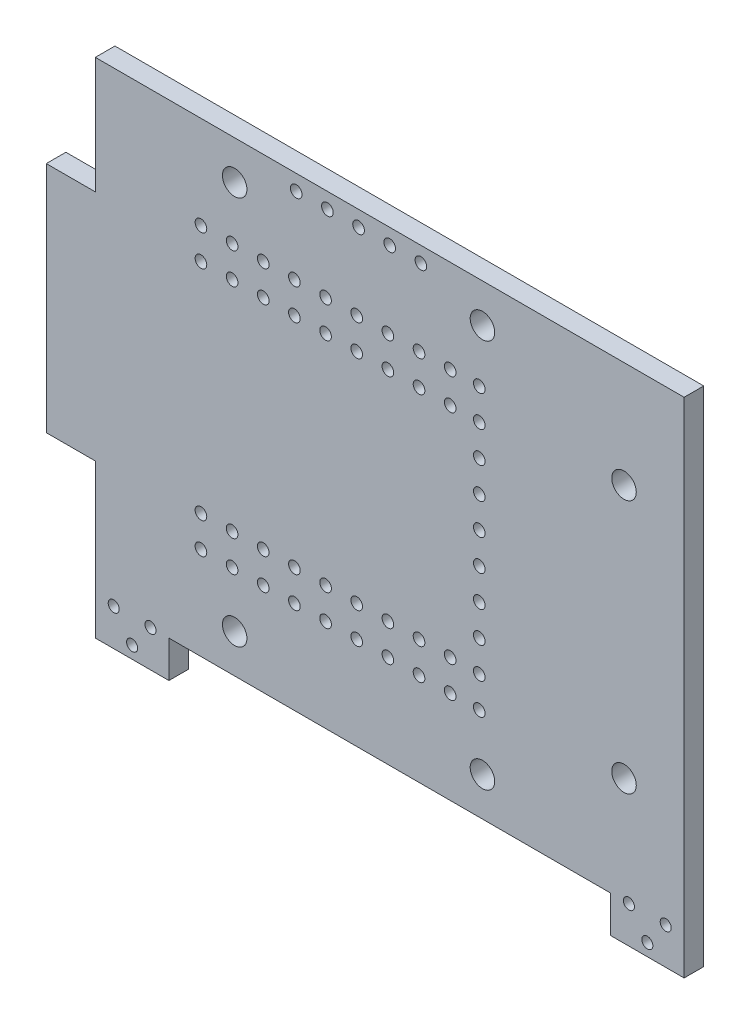
SolidWorks part; units mm, degrees
ref_plane "Front" through (0, 0, 0) normal (0, 0, 1) x (1, 0, 0)
ref_plane "Top" through (0, 0, 0) normal (0, 1, 0) x (1, 0, 0)
ref_plane "Right" through (0, 0, 0) normal (1, 0, 0) x (0, 0, -1)
sketch "草图1" plane through (0, 0, 0) normal (0, 0, 1) x (1, 0, 0)
  line L0 (0, 19.1903) -> (0, -26.9933) construction
  line L1 (-20.5, 19) -> (27.5, 19)
  line L2 (-20.5, 19) -> (-20.5, -19)
  line L3 (-20.5, -19) -> (27.5, -19)
  line L4 (27.5, 19) -> (27.5, -19)
  line L5 (-28.5476, 0) -> (37.8731, 0) construction
  dimension "D1" = 38
  dimension "D2" = 27.5
  dimension "D3" = 20.5
extrude "凸台-拉伸1" add sketch "草图1" against normal blind 1.6
ref_plane "基准面1" through (3.5, 0, 0) normal (1, 0, 0) x (0, 0, -1)
ref_plane "基准面2" through (0, 0, 0) normal (0, -1, 0) x (-1, 0, 0)
sketch "草图5" plane through (0, 0, 0) normal (0, 0, 1) x (1, 0, 0)
  circle A0 centre (-9.14, 15.85) radius 1
  circle A1 centre (11.06, 15.85) radius 1
  circle A2 centre (22.6, 10.35) radius 1
  circle A3 centre (22.6, -10.35) radius 1
  circle A4 centre (-11.89, 8.89) radius 0.475 construction
  circle A5 centre (-9.35, 8.89) radius 0.475 construction
  circle A6 centre (-6.81, 8.89) radius 0.475 construction
  circle A7 centre (-4.27, 8.89) radius 0.475 construction
  circle A8 centre (-11.89, 11.43) radius 0.475 construction
  circle A9 centre (-9.35, 11.43) radius 0.475 construction
  circle A10 centre (-6.81, 11.43) radius 0.475 construction
  circle A11 centre (-4.27, 11.43) radius 0.475 construction
  circle A12 centre (-1.73, 11.43) radius 0.475 construction
  circle A13 centre (0.81, 11.43) radius 0.475 construction
  circle A14 centre (3.35, 11.43) radius 0.475 construction
  circle A15 centre (-1.73, 8.89) radius 0.475 construction
  circle A16 centre (0.81, 8.89) radius 0.475 construction
  circle A17 centre (3.35, 8.89) radius 0.475 construction
  circle A18 centre (5.89, 8.89) radius 0.475 construction
  circle A19 centre (8.43, 8.89) radius 0.475 construction
  circle A20 centre (5.89, 11.43) radius 0.475 construction
  circle A21 centre (8.43, 11.43) radius 0.475 construction
  circle A22 centre (10.8, 11.43) radius 0.475 construction
  circle A23 centre (10.8, 8.89) radius 0.475 construction
  circle A24 centre (10.8, 6.35) radius 0.475 construction
  circle A25 centre (10.8, 3.81) radius 0.475 construction
  circle A26 centre (10.8, 1.27) radius 0.475 construction
  circle A27 centre (10.8, -1.27) radius 0.475 construction
  circle A28 centre (10.8, -3.81) radius 0.475 construction
  circle A29 centre (10.8, -6.35) radius 0.475 construction
  circle A30 centre (-11.89, -8.89) radius 0.475 construction
  circle A31 centre (-9.35, -8.89) radius 0.475 construction
  circle A32 centre (-6.81, -8.89) radius 0.475 construction
  circle A33 centre (-4.27, -8.89) radius 0.475 construction
  circle A34 centre (-1.73, -8.89) radius 0.475 construction
  circle A35 centre (0.81, -8.89) radius 0.475 construction
  circle A36 centre (3.35, -8.89) radius 0.475 construction
  circle A37 centre (5.89, -8.89) radius 0.475 construction
  circle A38 centre (8.43, -8.89) radius 0.475 construction
  circle A39 centre (10.8, -8.89) radius 0.475 construction
  circle A40 centre (-11.89, -11.43) radius 0.475 construction
  circle A41 centre (-9.35, -11.43) radius 0.475 construction
  circle A42 centre (-6.81, -11.43) radius 0.475 construction
  circle A43 centre (-4.27, -11.43) radius 0.475 construction
  circle A44 centre (-1.73, -11.43) radius 0.475 construction
  circle A45 centre (0.81, -11.43) radius 0.475 construction
  circle A46 centre (3.35, -11.43) radius 0.475 construction
  circle A47 centre (5.89, -11.43) radius 0.475 construction
  circle A48 centre (8.43, -11.43) radius 0.475 construction
  circle A49 centre (10.8, -11.43) radius 0.475 construction
  circle A55 centre (3.5, 17.73) radius 0.475 construction
  circle A56 centre (6.04, 17.73) radius 0.475 construction
  circle A57 centre (0.96, 17.73) radius 0.475 construction
  circle A58 centre (-4.12, 17.73) radius 0.475 construction
  circle A59 centre (-1.58, 17.73) radius 0.475 construction
  circle A64 centre (-11.89, 8.89) radius 0.475
  circle A65 centre (-9.35, 8.89) radius 0.475
  circle A66 centre (-6.81, 8.89) radius 0.475
  circle A67 centre (-4.27, 8.89) radius 0.475
  circle A68 centre (-11.89, 11.43) radius 0.475
  circle A69 centre (-9.35, 11.43) radius 0.475
  circle A70 centre (-6.81, 11.43) radius 0.475
  circle A71 centre (-4.27, 11.43) radius 0.475
  circle A72 centre (-1.73, 11.43) radius 0.475
  circle A73 centre (0.81, 11.43) radius 0.475
  circle A74 centre (3.35, 11.43) radius 0.475
  circle A75 centre (-1.73, 8.89) radius 0.475
  circle A76 centre (0.81, 8.89) radius 0.475
  circle A77 centre (3.35, 8.89) radius 0.475
  circle A78 centre (5.89, 8.89) radius 0.475
  circle A79 centre (8.43, 8.89) radius 0.475
  circle A80 centre (5.89, 11.43) radius 0.475
  circle A81 centre (8.43, 11.43) radius 0.475
  circle A82 centre (10.8, 11.43) radius 0.475
  circle A83 centre (10.8, 8.89) radius 0.475
  circle A84 centre (10.8, 6.35) radius 0.475
  circle A85 centre (10.8, 3.81) radius 0.475
  circle A86 centre (10.8, 1.27) radius 0.475
  circle A87 centre (10.8, -1.27) radius 0.475
  circle A88 centre (10.8, -3.81) radius 0.475
  circle A89 centre (10.8, -6.35) radius 0.475
  circle A90 centre (-11.89, -8.89) radius 0.475
  circle A91 centre (-9.35, -8.89) radius 0.475
  circle A92 centre (-6.81, -8.89) radius 0.475
  circle A93 centre (-4.27, -8.89) radius 0.475
  circle A94 centre (-1.73, -8.89) radius 0.475
  circle A95 centre (0.81, -8.89) radius 0.475
  circle A96 centre (3.35, -8.89) radius 0.475
  circle A97 centre (5.89, -8.89) radius 0.475
  circle A98 centre (8.43, -8.89) radius 0.475
  circle A99 centre (10.8, -8.89) radius 0.475
  circle A100 centre (-11.89, -11.43) radius 0.475
  circle A101 centre (-9.35, -11.43) radius 0.475
  circle A102 centre (-6.81, -11.43) radius 0.475
  circle A103 centre (-4.27, -11.43) radius 0.475
  circle A104 centre (-1.73, -11.43) radius 0.475
  circle A105 centre (0.81, -11.43) radius 0.475
  circle A106 centre (3.35, -11.43) radius 0.475
  circle A107 centre (5.89, -11.43) radius 0.475
  circle A108 centre (8.43, -11.43) radius 0.475
  circle A109 centre (10.8, -11.43) radius 0.475
  circle A115 centre (3.5, 17.73) radius 0.475
  circle A116 centre (6.04, 17.73) radius 0.475
  circle A117 centre (0.96, 17.73) radius 0.475
  circle A118 centre (-4.12, 17.73) radius 0.475
  circle A119 centre (-1.58, 17.73) radius 0.475
  circle A122 centre (11.06, -15.85) radius 1
  circle A123 centre (-9.14, -15.85) radius 1
  point P1 (0, 0)
  point P2 (0, 0)
  point P14 (0, 0)
  point P16 (0, 0)
  point P17 (0, 0)
  point P20 (0, 0)
  dimension "D1" = 2
  dimension "D2" = 2
  dimension "D3" = 2
  dimension "D4" = 2
  dimension "D5" = 2
  dimension "D6" = 2
extrude "切除-拉伸1" cut sketch "草图5" against normal up to next (1.6 mm away)
sketch "草图8" plane through (-20.5, 0, 0) normal (-1, 0, 0) x (0, 0, 1)
  line L0 (-1.6, 0) -> (13.2393, 0) construction
  line L1 (-1.6, 19) -> (-1.6, -19) construction
  line L2 (0, 19) -> (0, -19) construction
  line L3 (-1.6, 9.5) -> (0, 9.5)
  line L4 (-1.6, 9.5) -> (-1.6, -9.5)
  line L5 (-1.6, -9.5) -> (0, -9.5)
  line L6 (0, 9.5) -> (0, -9.5)
  dimension "D1" = 19
extrude "凸台-拉伸3" add sketch "草图8" along normal blind 4
sketch "草图9" plane through (0, -19, 0) normal (0, -1, 0) x (1, 0, 0)
  line L0 (-20.5, 0) -> (27.5, 0) construction
  line L1 (-20.5, -1.6) -> (-14.5, -1.6)
  line L2 (-20.5, -1.6) -> (-20.5, 0)
  line L3 (-20.5, 0) -> (-14.5, 0)
  line L4 (-14.5, -1.6) -> (-14.5, 0)
  line L6 (27.5, -1.6) -> (21.5, -1.6)
  line L7 (27.5, -1.6) -> (27.5, 0)
  line L8 (27.5, 0) -> (21.5, 0)
  line L9 (21.5, -1.6) -> (21.5, 0)
  dimension "D1" = 6
  dimension "D2" = 6
extrude "凸台-拉伸4" add sketch "草图9" along normal blind 3
sketch "草图10" plane through (0, 0, 0) normal (0, 0, 1) x (1, 0, 0)
  line L0 (-20.5, -9.5) -> (-20.5, -22) construction
  line L1 (21.5, -22) -> (21.5, -19) construction
  line L2 (27.5, -22) -> (21.5, -22) construction
  line L3 (-14.5, -22) -> (-20.5, -22) construction
  circle A0 centre (-19, -19) radius 0.45
  circle A1 centre (-16, -19) radius 0.45
  circle A2 centre (-17.5, -21) radius 0.45
  circle A3 centre (23, -19) radius 0.45
  circle A4 centre (26, -19) radius 0.45
  circle A5 centre (24.5, -21) radius 0.45
  point P8 (0, 0)
  point P17 (25.9732, -19.3563)
  point P18 (22.9385, -19.3563)
  point P19 (24.5, -21)
  dimension "D1" = 0.9
  dimension "D2" = 0.9
  dimension "D3" = 0.9
  dimension "D10" = 0.9
  dimension "D11" = 0.9
  dimension "D12" = 0.9
  dimension "D4" = 3
  dimension "D5" = 2
  dimension "D6" = 1.5
  dimension "D7" = 3
  dimension "D8" = 3
  dimension "D9" = 1.5
  dimension "D13" = 3
  dimension "D14" = 2
  dimension "D15" = 3
  dimension "D16" = 1.5
extrude "切除-拉伸2" cut sketch "草图10" against normal up to next
